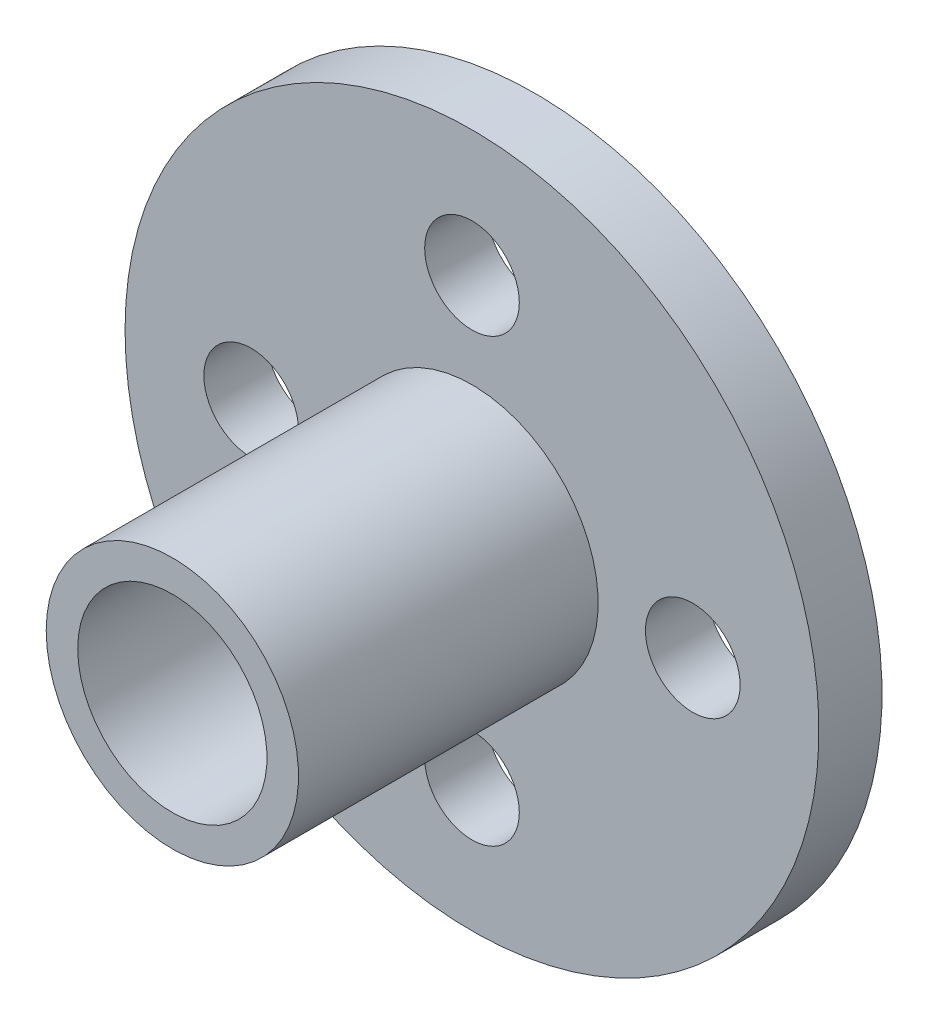
SolidWorks part; units mm, degrees
ref_plane "前视基准面" through (0, 0, 0) normal (0, 0, 1) x (1, 0, 0)
ref_plane "上视基准面" through (0, 0, 0) normal (0, 1, 0) x (1, 0, 0)
ref_plane "右视基准面" through (0, 0, 0) normal (1, 0, 0) x (0, 0, -1)
other "Configuration Table"
sketch "草图1" plane through (0, 0, 0) normal (0, 1, 0) x (1, 0, 0)
  line L0 (0, 0) -> (-8, 0)
  line L1 (-8, 0) -> (-8, -2)
  line L2 (-8, -2) -> (-1, -2)
  line L3 (-1, -2) -> (-1, -11.5)
  line L4 (-1, -11.5) -> (0, -11.5)
  line L5 (0, -11.5) -> (0, 0)
  line L6 (3, 3.3558) -> (3, -20.1995) construction
  point P9 (3, -8.4219)
  dimension "D1" = 11.5
  dimension "D2" = 2
  dimension "D3" = 1
  dimension "D4" = 3
  dimension "D5" = 8
revolve "旋转1" add sketch "草图1" angle 360 about L6
sketch "草图2" plane through (0, 0, 0) normal (0, 0, -1) x (-1, 0, 0)
  line L0 (-3, 7) -> (-3, 0) construction
  circle A0 centre (-3, 7) radius 1.5
  circle A1 centre (4, 0) radius 1.5
  circle A2 centre (-3, -7) radius 1.5
  circle A3 centre (-10, 0) radius 1.5
  dimension "D1" = 4
extrude "切除-拉伸1" cut sketch "草图2" against normal blind 10
